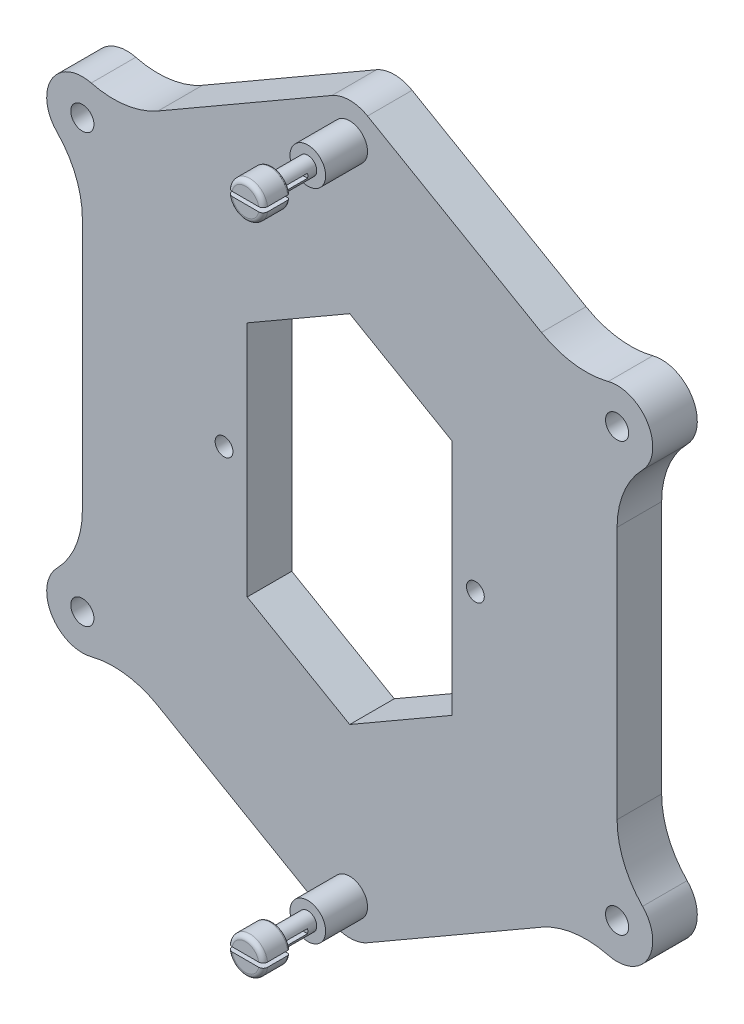
SolidWorks part; units mm, degrees
ref_plane "Front Plane" through (0, 0, 0) normal (1, 0, 0) x (0, 1, 0)
ref_plane "Top Plane" through (0, 0, 0) normal (0, 0, 1) x (0, 1, 0)
ref_plane "Right Plane" through (0, 0, 0) normal (0, 1, 0) x (-1, 0, 0)
sketch "Sketch1" plane through (0, 0, 0) normal (0, 0, 1) x (0, 1, 0)
  line L1 (26.0415, 8.0948) -> (40.2073, -16.4411)
  line L2 (40.2073, -20.4411) -> (26.0415, -44.977)
  line L3 (20.0415, -48.4411) -> (-19.9585, -48.4411)
  line L4 (-19.9585, 11.5589) -> (20.0415, 11.5589)
  line L5 (0.0415, 11.5589) -> (0.0415, -48.4411) construction
  line L6 (-40.1243, -20.4411) -> (-25.9585, -44.977)
  line L7 (-25.9585, 8.0948) -> (-40.1243, -16.4411)
  arc A0 (20.0415, 11.5589) -> (26.0415, 8.0948) centre (24.0415, 11.5589) cw
  arc A1 (40.2073, -16.4411) -> (40.2073, -20.4411) centre (36.7432, -18.4411) cw
  arc A2 (26.0415, -44.977) -> (20.0415, -48.4411) centre (24.0415, -48.4411) cw
  arc A3 (-25.9585, -44.977) -> (-19.9585, -48.4411) centre (-23.9585, -48.4411) ccw
  arc A4 (-40.1243, -16.4411) -> (-40.1243, -20.4411) centre (-36.6602, -18.4411) ccw
  arc A5 (-19.9585, 11.5589) -> (-25.9585, 8.0948) centre (-23.9585, 11.5589) ccw
  point P13 (0.0415, -18.4411)
  dimension "D3" = 4
  dimension "D4" = 4
  dimension "D1" = 48
  dimension "D2" = 60
  dimension "D5" = 120
extrude "Boss-Extrude1" add sketch "Sketch1" along normal blind 5
sketch "Sketch2" plane through (0, 0, 5) normal (0, 0, 1) x (1, 0, 0)
  line L0 (-11.5589, 0.0415) -> (48.4411, 0.0415) construction
  line L1 (-11.5589, 20.0415) -> (-11.5589, -19.9585) construction
  line L2 (48.4411, -19.9585) -> (48.4411, 20.0415) construction
  circle A0 centre (18.4411, -36.6602) radius 2
  circle A1 centre (18.4411, 36.7432) radius 2
  dimension "D1" = 4
extrude "Boss-Extrude2" add sketch "Sketch2" along normal blind 11.7
sketch "Sketch3" plane through (0, 0, 5) normal (0, 0, 1) x (1, 0, 0)
  line L0 (-11.5589, 0.0415) -> (48.4411, 0.0415) construction
  line L1 (-11.5589, 20.0415) -> (-11.5589, -19.9585) construction
  line L2 (48.4411, -19.9585) -> (48.4411, 20.0415) construction
  line L3 (18.4411, 40.7432) -> (18.4411, -40.6602) construction
  arc A0 (20.4411, 40.2073) -> (16.4411, 40.2073) centre (18.4411, 36.7432) ccw construction
  arc A1 (16.4411, -40.1243) -> (20.4411, -40.1243) centre (18.4411, -36.6602) ccw construction
  circle A2 centre (-11.5589, 24.0415) radius 1.3
  circle A3 centre (48.4411, 24.0415) radius 1.3
  circle A4 centre (48.4411, -23.9585) radius 1.3
  circle A5 centre (-11.5589, -23.9585) radius 1.3
  dimension "D1" = 2.6
extrude "Cut-Extrude1" cut sketch "Sketch3" against normal up to next
fillet "Fillet1" radius 10 8 edges at (44.977, 26.0415, 2.5) (48.4411, 20.0415, 2.5) (48.4411, -19.9585, 2.5) (44.977, -25.9585, 2.5) (-8.0948, -25.9585, 2.5) (-11.5589, -19.9585, 2.5) (-11.5589, 20.0415, 2.5) (-8.0948, 26.0415, 2.5)
fillet "Fillet3" radius 0.5 2 edges at (16.4411, 36.7432, 16.7) (20.4411, -36.6602, 16.7)
sketch "Sketch9" plane through (0, 0, 5) normal (0, 0, 1) x (1, 0, 0)
  line L12 (18.4411, -19.9171) -> (29.9411, -13.2776)
  line L13 (29.9411, -13.2776) -> (29.9411, 13.3605)
  line L14 (29.9411, 13.3605) -> (18.4411, 20)
  line L15 (18.4411, 20) -> (6.9411, 13.3605)
  line L16 (6.9411, 13.3605) -> (6.9411, -13.2776)
  line L17 (6.9411, -13.2776) -> (18.4411, -19.9171)
  line L18 (18.4411, -19.9171) -> (29.9411, -13.2776)
  line L19 (29.9411, -13.2776) -> (29.9411, 13.3605)
  line L20 (29.9411, 13.3605) -> (18.4411, 20)
  line L21 (18.4411, 20) -> (6.9411, 13.3605)
  line L22 (6.9411, 13.3605) -> (6.9411, -13.2776)
  line L23 (6.9411, -13.2776) -> (18.4411, -19.9171)
  dimension "D1" = 18.5
extrude "Cut-Extrude4" cut sketch "Sketch9" against normal up to next
sketch "Sketch10" plane through (0, 0, 5) normal (0, 0, 1) x (1, 0, 0)
  line L0 (18.4411, 40.7432) -> (18.4411, -40.6602) construction
  line L1 (-11.5589, 0.0415) -> (48.4411, 0.0415) construction
  line L2 (-11.5589, 14.2435) -> (-11.5589, -14.1606) construction
  line L3 (48.4411, -14.1606) -> (48.4411, 14.2435) construction
  arc A0 (20.4411, 40.2073) -> (16.4411, 40.2073) centre (18.4411, 36.7432) ccw construction
  arc A1 (16.4411, -40.1243) -> (20.4411, -40.1243) centre (18.4411, -36.6602) ccw construction
  circle A6 centre (4.3411, 0.0415) radius 1
  circle A7 centre (32.5411, 0.0415) radius 1
  dimension "D1" = 2
  dimension "D2" = 14.1
extrude "Cut-Extrude5" cut sketch "Sketch10" against normal up to next
sketch3d "3DSketch1"
  line L0 (18.4411, -40.6602, 5) -> (18.4411, 40.7432, 5) construction
  arc A2 (16.4411, -40.1243, 5) -> (20.4411, -40.1243, 5) centre (18.4411, -36.6602, 5) ccw construction
  arc A3 (20.4411, 40.2073, 5) -> (16.4411, 40.2073, 5) centre (18.4411, 36.7432, 5) ccw construction
  circle A4 centre (18.4411, 36.7432, 16.7) radius 1.5 construction
  point P5 (18.4411, -36.6602, 9)
  point P9 (18.4411, 36.7432, 9)
  point P12 (18.4411, 36.7432, 18.2)
sketch "Sketch20" plane through (18.4411, 0, 0) normal (1, 0, 0) x (0, 1, 0)
  line L6 (36.7432, 16.7) -> (36.7432, 5) construction
  line L7 (38.2432, 16.7) -> (35.2432, 16.7) construction
  line L8 (-40.6602, 5) -> (40.7432, 5) construction
  line L9 (38.7432, 5) -> (38.7432, 16.2) construction
  line L10 (38.7432, 13.7) -> (37.7432, 13.7)
  line L11 (38.7432, 13.7) -> (38.7432, 9.7)
  line L12 (38.7432, 9.7) -> (37.7432, 9.7)
  line L13 (37.7432, 13.7) -> (37.7432, 9.7)
  line L14 (0.0415, 5) -> (0, 0) construction
  dimension "D1" = 1
  dimension "D2" = 4
  dimension "D3" = 3
revolve "Cut-Revolve1" cut sketch "Sketch20" angle 360 about L6
sketch "Sketch21" plane through (18.4411, 0, 0) normal (1, 0, 0) x (0, 1, 0)
  line L0 (38.2432, 16.7) -> (35.2432, 16.7) construction
  line L1 (36.9932, 16.7) -> (36.4932, 16.7)
  line L2 (36.9932, 16.7) -> (36.9932, 10.7)
  line L3 (36.9932, 10.7) -> (36.4932, 10.7)
  line L4 (36.4932, 16.7) -> (36.4932, 10.7)
  line L5 (36.7432, 16.7) -> (36.7432, 5) construction
  line L6 (-40.6602, 5) -> (40.7432, 5) construction
  point P10 (36.7432, 16.7)
  dimension "D1" = 0.5
  dimension "D2" = 6
extrude "Cut-Extrude6" cut sketch "Sketch21" against normal up to next and the other way up to next
sketch "Sketch24" plane through (18.4411, 0, 0) normal (1, 0, 0) x (0, 1, 0)
  line L0 (-36.6602, 16.7) -> (-36.6602, 5) construction
  line L1 (-35.1602, 16.7) -> (-38.1602, 16.7) construction
  line L2 (-40.6602, 5) -> (40.7432, 5) construction
  line L3 (-38.6602, 16.2) -> (-38.6602, 5) construction
  line L4 (-38.6602, 13.7) -> (-37.6602, 13.7)
  line L5 (-38.6602, 13.7) -> (-38.6602, 9.7)
  line L6 (-38.6602, 9.7) -> (-37.6602, 9.7)
  line L7 (-37.6602, 13.7) -> (-37.6602, 9.7)
  dimension "D1" = 3
  dimension "D2" = 4
  dimension "D3" = 1
revolve "Cut-Revolve2" cut sketch "Sketch24" angle 360 about L0
sketch "Sketch25" plane through (18.4411, 0, 0) normal (1, 0, 0) x (0, 1, 0)
  line L0 (-35.1602, 16.7) -> (-38.1602, 16.7) construction
  line L1 (-36.4102, 16.7) -> (-36.9102, 16.7)
  line L2 (-36.4102, 16.7) -> (-36.4102, 10.7)
  line L3 (-36.4102, 10.7) -> (-36.9102, 10.7)
  line L4 (-36.9102, 16.7) -> (-36.9102, 10.7)
  line L5 (-36.6602, 9.7) -> (-36.6602, 16.7) construction
  line L6 (-34.6602, 9.7) -> (-38.6602, 9.7) construction
  point P10 (-36.6602, 16.7)
  dimension "D1" = 0.5
  dimension "D2" = 6
extrude "Cut-Extrude7" cut sketch "Sketch25" against normal up to next and the other way up to next
fillet "Fillet4" radius 0.25 4 edges at (18.4411, -34.6602, 13.7) (18.4411, -38.6602, 13.7) (18.4411, 38.7432, 13.7) (18.4411, 34.7432, 13.7)
